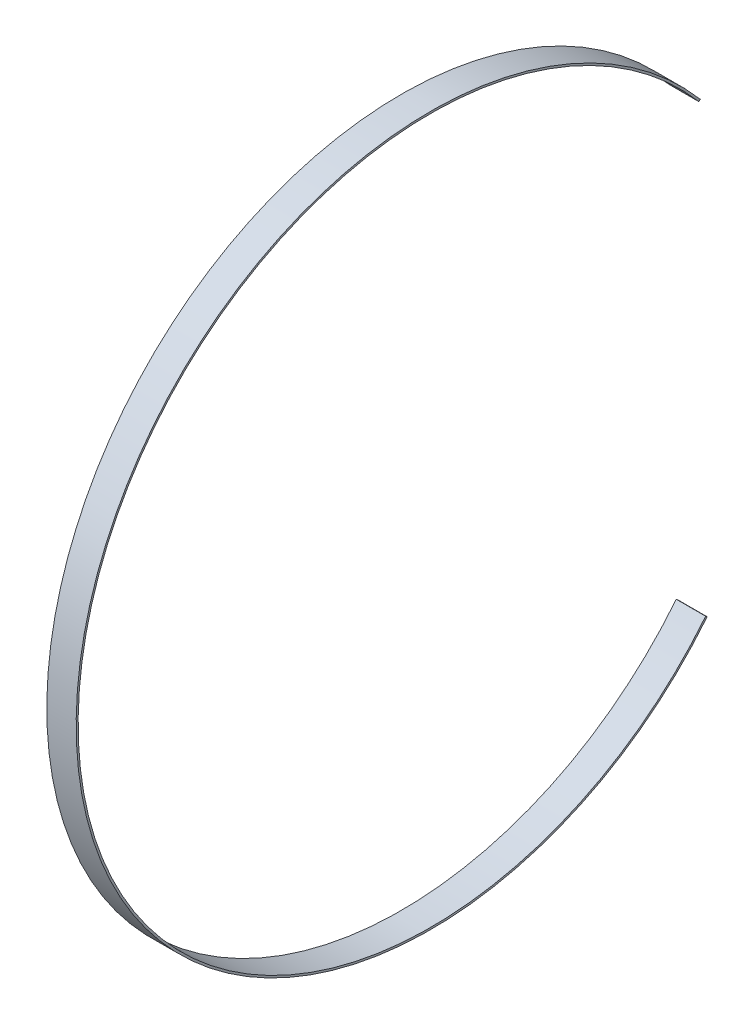
SolidWorks part; units mm, degrees
ref_plane "Front Plane" through (0, 0, 0) normal (0, 0, 1) x (1, 0, 0)
ref_plane "Top Plane" through (0, 0, 0) normal (0, 1, 0) x (1, 0, 0)
ref_plane "Right Plane" through (0, 0, 0) normal (1, 0, 0) x (0, 0, -1)
sketch "Sketch1" plane through (0, 0, 0) normal (1, 0, 0) x (0, 0, -1)
  arc A0 (347.9343, 296.6034) -> (356.7665, -285.9187) centre (0, 0) ccw
extrude "Extrude-Thin1" add sketch "Sketch1" along normal blind 38.1 thin
